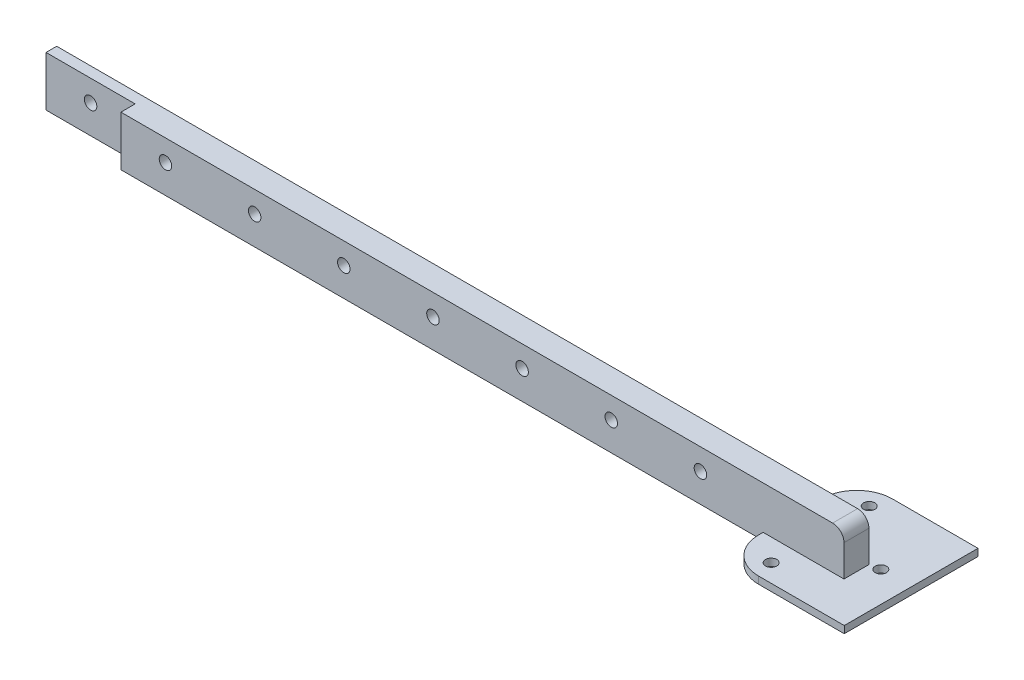
SolidWorks part; units mm, degrees
ref_plane "Front Plane" through (0, 0, 0) normal (0, 0, 1) x (1, 0, 0)
ref_plane "Top Plane" through (0, 0, 0) normal (0, 1, 0) x (1, 0, 0)
ref_plane "Right Plane" through (0, 0, 0) normal (1, 0, 0) x (0, 0, -1)
sketch "TopSketch1" plane through (0, 0, 0) normal (0, 1, 0) x (1, 0, 0)
  line L0 (0, 0) -> (34, 0)
  line L1 (34, 0) -> (34, 37.5)
  line L2 (34, 37.5) -> (0, 37.5)
  line L3 (0, 37.5) -> (0, 19.25)
  line L7 (0, 11.25) -> (0, 0)
  line L8 (0, 11.25) -> (-205.08, 11.25)
  line L9 (-205.08, 11.25) -> (-205.08, 19.25)
  line L10 (-205.08, 19.25) -> (0, 19.25)
  circle A0 centre (8.5, 32.5) radius 1.59
  circle A1 centre (8.5, 5) radius 1.59
  circle A3 centre (25.5, 18.75) radius 1.59
  dimension "D6" = 3.18
  dimension "D1" = 37.5
  dimension "D2" = 34
  dimension "D5" = 8.5
  dimension "D7" = 5
  dimension "D8" = 5
  dimension "D3" = 205.08
  dimension "D4" = 8
  dimension "D9" = 8.5
  dimension "D10" = 18.75
  dimension "D11" = 11.25
  dimension "D12" = 18.25
  dimension "D13" = 239.08
extrude "TopBoss-Extrude1" add sketch "TopSketch1" along normal blind 2
fillet "Fillet1" radius 10 2 edges at (0, 1, 0) (0, 1, -37.5)
sketch "LinearRailHEightSketch2" plane through (0, 2, 0) normal (0, 1, 0) x (1, 0, 0)
  line L1 (-205.08, 18.25) -> (22.6667, 18.25)
  line L2 (-205.08, 18.25) -> (-205.08, 11.25)
  line L3 (-205.08, 11.25) -> (22.6667, 11.25)
  line L4 (22.6667, 18.25) -> (22.6667, 11.25)
  line L5 (-205.08, 19.25) -> (-205.08, 11.25) construction
  line L6 (-205.08, 11.25) -> (0, 11.25) construction
  line L8 (34, 0) -> (34, 37.5) construction
  line L9 (0, 19.25) -> (-205.08, 19.25) construction
  dimension "D2" = 11.3333
  dimension "D1" = 1
extrude "LinearRailHeightBoss-Extrude2" add sketch "LinearRailHEightSketch2" along normal blind 12
sketch "LinearRailHolesSketch3" plane through (0, 0, -11.25) normal (0, 0, 1) x (1, 0, 0)
  line L0 (0, 2) -> (22.6667, 2) construction
  line L1 (-205.08, 14) -> (-205.08, 0) construction
  circle A0 centre (-192.58, 8) radius 1.75
  circle A1 centre (-167.58, 8) radius 1.75
  circle A2 centre (-142.58, 8) radius 1.75
  circle A3 centre (-117.58, 8) radius 1.75
  circle A4 centre (-92.58, 8) radius 1.75
  circle A5 centre (-67.58, 8) radius 1.75
  circle A6 centre (-42.58, 8) radius 1.75
  circle A7 centre (-17.58, 8) radius 1.75
  dimension "D4" = 8
  dimension "D1" = 3.5
  dimension "D2" = 6
  dimension "D3" = 12.5
extrude "LinearRailHolesCut-Extrude1" cut sketch "LinearRailHolesSketch3" against normal through all
sketch "ConnectingPlateSketch1" plane through (0, 0, -11.25) normal (0, 0, 1) x (1, 0, 0)
  line L0 (-205.08, 0) -> (0, 0) construction
  line L1 (-205.08, 14) -> (-180.08, 14)
  line L2 (-205.08, 14) -> (-205.08, 0)
  line L3 (-205.08, 0) -> (-180.08, 0)
  line L4 (-180.08, 14) -> (-180.08, 0)
  line L5 (-205.08, 14) -> (22.6667, 14) construction
  line L6 (-205.08, 14) -> (-205.08, 0) construction
  dimension "D1" = 25
extrude "ConnectingPlateCut-Extrude1" cut sketch "ConnectingPlateSketch1" against normal blind 4
fillet "Fillet2" radius 3.175 1 edges at (22.6667, 14, -14.75)
equation "\"GABDepth\"= \"GABDistanceFromBackToFirstPulley\" + \"GABPulleyDDistanceBetween\" + \"GABDistanceFromPulleyToFront\""
equation "\"GABWidth\"= \"StandardWallThickness\" + \"GABDistanceFromLSideToPulley\" + \"GABPulleyWDistanceBetween\" + \"GABDistanceFromPulleyToRSide\""
equation "\"StandardWallThickness\"= 3mm"
equation "\"LinearRailWidth\"= 12mm'Spec"
equation "\"LinearRailHeight\"= 8mm'Spec"
equation "\"GABLRClampHoleOffsetFromSide\"= 5mm"
equation "\"GABDistanceFromBackToFirstPulley\"= 13.5mm"
equation "\"GABPulleyDDistanceBetween\"= 12.5mm'From the100"
equation "\"GABPulleyWDistanceBetween\"= 14.5mm'From the100"
equation "\"GABDistanceFromPulleyToFront\"= 8mm"
equation "\"GABDistanceFromLSideToPulley\"= 9.5mm + \"StandardWallThickness\""
equation "\"GABDistanceFromPulleyToRSide\"= 7.5mm"
equation "\"GABClampBaseHeight\"= 2mm"
equation "\"LinearRailHoleDiameter\"= 3.5mm'Spec"
equation "\"GABDistanceToFrontRearClampHoles\"= 8.5mm"
equation "\"D1@TopSketch1\" = \"GABWidth\""
equation "\"D2@TopSketch1\"=\"GABDepth\""
equation "\"D5@TopSketch1\" = \"GABDistanceToFrontRearClampHoles\""
equation "\"D7@TopSketch1\" = \"GABLRClampHoleOffsetFromSide\""
equation "\"D8@TopSketch1\" = \"GABLRClampHoleOffsetFromSide\""
equation "\"D1@TopBoss-Extrude1\" = \"GABClampBaseHeight\""
equation "\"RailThickness\"= .125in'Spec"
equation "\"D4@TopSketch1\"=\"LinearRailHeight\""
equation "\"D1@LinearRailHeightBoss-Extrude2\" = \"LinearRailWidth\""
equation "\"D1@LinearRailHolesSketch3\" = \"LinearRailHoleDiameter\""
equation "\"D2@LinearRailHolesSketch3\" = \"LinearRailWidth\" / 2"
equation "\"D9@TopSketch1\"=\"GABDistanceToFrontRearClampHoles\""
equation "\"D2@LinearRailHEightSketch2\"=\"GABDepth\"/3"
equation "\"LinearRailHoleDistance\"= 25mm'Spec"
equation "\"D11@TopSketch1\"=\"GABWidth\"/2 -\"LinearRailHeight\" + 1/2"
equation "\"D1@ConnectingPlateSketch1\" = \"LinearRailHoleDistance\""
equation "\"D1@ConnectingPlateCut-Extrude1\" = \"LinearRailHeight\" / 2"
equation "\"D1@Fillet2\"=\"RailThickness\""
